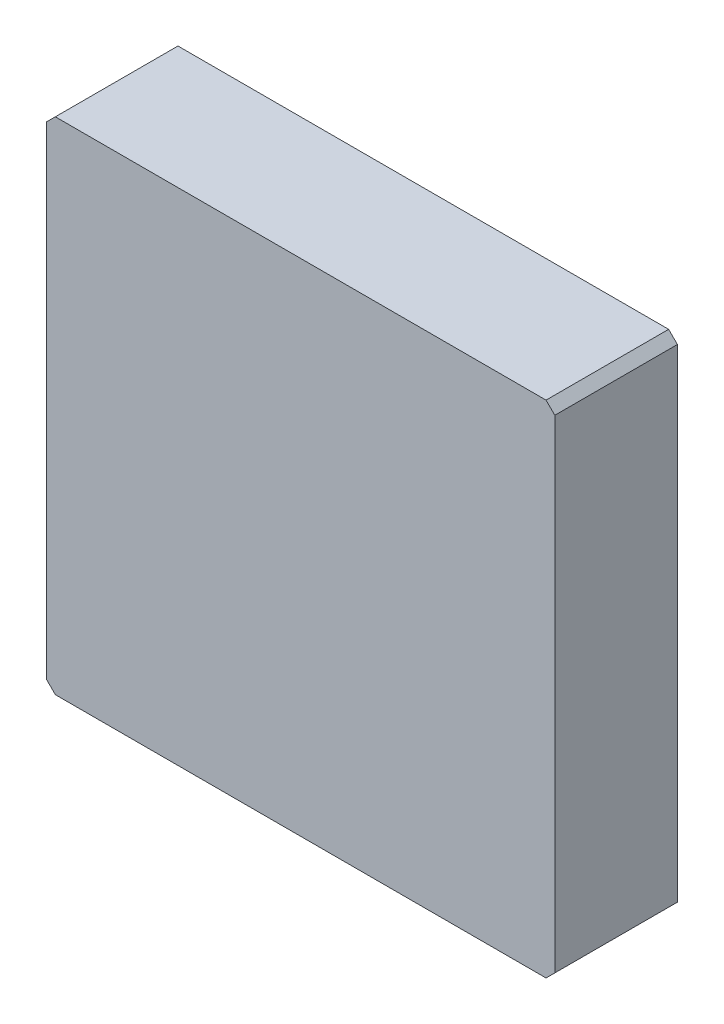
SolidWorks part; units mm, degrees
ref_plane "Front Plane" through (0, 0, 0) normal (0, 0, 1) x (1, 0, 0)
ref_plane "Top Plane" through (0, 0, 0) normal (0, 1, 0) x (1, 0, 0)
ref_plane "Right Plane" through (0, 0, 0) normal (1, 0, 0) x (0, 0, -1)
sketch "Sketch1" plane through (0, 0, 0) normal (0, 0, 1) x (1, 0, 0)
  line L0 (0, 199.644) -> (3.556, 203.2)
  line L1 (3.556, 0) -> (202.7936, 0)
  line L2 (0, 3.556) -> (0, 199.644)
  line L3 (3.556, 203.2) -> (202.7936, 203.2)
  line L4 (206.3496, 3.556) -> (206.3496, 199.644)
  line L5 (202.7936, 203.2) -> (206.3496, 199.644)
  line L6 (202.7936, 0) -> (206.3496, 3.556)
  line L7 (0, 3.556) -> (3.556, 0)
  point P0 (0, 0)
  point P1 (206.3496, 203.2)
  point P2 (0, 203.2)
  point P3 (206.3496, 0)
  dimension "D1" = 203.2
  dimension "D2" = 206.3496
  dimension "D3" = 3.556
  dimension "D4" = 45
  dimension "D5" = 3.556
  dimension "D6" = 45
  dimension "D7" = 3.556
  dimension "D8" = 45
  dimension "D9" = 3.556
  dimension "D10" = 45
extrude "Boss-Extrude1" add sketch "Sketch1" along normal blind 49.784
sketch "Sketch2" plane through (0, 0, 0) normal (0, 0, -1) x (-1, 0, 0)
  line L0 (-192.8876, 181.8386) -> (-192.8876, 21.3614)
  line L1 (-184.7342, 13.208) -> (-65.913, 13.208)
  line L2 (-57.7596, 21.3614) -> (-57.7596, 100.076)
  line L3 (-54.2036, 103.632) -> (-21.3614, 103.632)
  line L4 (-13.208, 111.7854) -> (-13.208, 181.8386)
  line L5 (-21.3614, 189.992) -> (-184.7342, 189.992)
  line L6 (-206.3496, 3.556) -> (-206.3496, 199.644) construction
  line L7 (-57.7596, 100.076) -> (-54.2036, 103.632)
  line L8 (-3.556, 0) -> (-202.7936, 0) construction
  arc A0 (-65.913, 13.208) -> (-57.7596, 21.3614) centre (-65.913, 21.3614) ccw
  arc A1 (-192.8876, 21.3614) -> (-184.7342, 13.208) centre (-184.7342, 21.3614) ccw
  arc A2 (-21.3614, 103.632) -> (-13.208, 111.7854) centre (-21.3614, 111.7854) ccw
  arc A3 (-13.208, 181.8386) -> (-21.3614, 189.992) centre (-21.3614, 181.8386) ccw
  arc A4 (-192.8876, 181.8386) -> (-184.7342, 189.992) centre (-184.7342, 181.8386) cw
  point P4 (-57.7596, 103.632)
  dimension "D9" = 8.1534
  dimension "D1" = 179.6796
  dimension "D2" = 13.462
  dimension "D3" = 3.556
  dimension "D4" = 45
  dimension "D5" = 135.128
  dimension "D6" = 176.784
  dimension "D7" = 13.208
  dimension "D8" = 103.632
extrude "Cut-Extrude1" cut sketch "Sketch2" against normal blind 31.877
